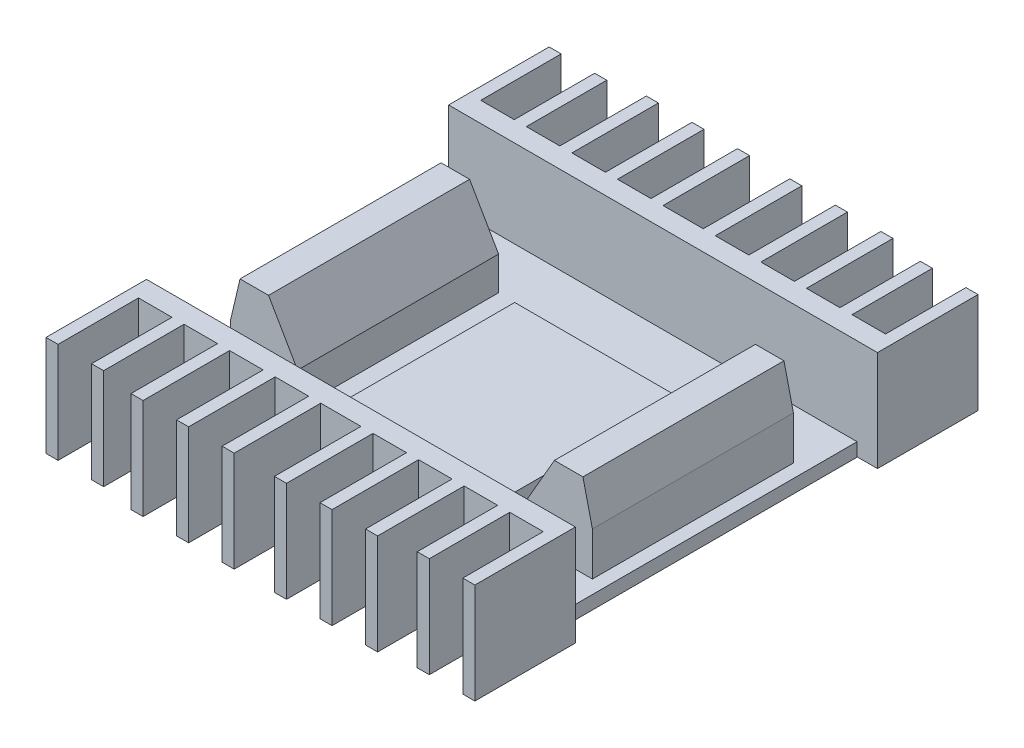
SolidWorks part; units mm, degrees
ref_plane "Front Plane" through (0, 0, 0) normal (0, 0, 1) x (1, 0, 0)
ref_plane "Top Plane" through (0, 0, 0) normal (0, 1, 0) x (1, 0, 0)
ref_plane "Right Plane" through (0, 0, 0) normal (1, 0, 0) x (0, 0, -1)
ref_plane "Plane1" through (0, 0, 0) normal (0, 0, 1) x (1, 0, 0)
ref_plane "Plane2" through (0, 0, 0) normal (0, 1, 0) x (1, 0, 0)
ref_plane "Plane3" through (0, 0, 0) normal (1, 0, 0) x (0, 0, -1)
sketch "Sketch2" plane through (0, 0, 0) normal (0, 1, 0) x (1, 0, 0)
  line L0 (-55, 0) -> (55, 0) construction
  line L2 (-57.5797, 0) -> (0.4203, 0)
  line L3 (-57.5797, 0) -> (-57.5797, -45)
  line L4 (-57.5797, -45) -> (0.4203, -45)
  line L5 (0.4203, 0) -> (0.4203, -45)
  dimension "D1" = 58
  dimension "D2" = 45
extrude "Boss-Extrude1" add sketch "Sketch2" along normal blind 2
sketch "Sketch3" plane through (0, 0, 0) normal (0, 1, 0) x (1, 0, 0)
  line L0 (3.4203, -45.0399) -> (-60.5797, -45.0399)
  line L1 (0.4203, -45) -> (0.4203, 0) construction
  line L2 (3.4203, -45.0399) -> (3.4203, -60.0399)
  line L3 (3.4203, -60.0399) -> (1.6203, -60.0399)
  line L4 (1.6203, -60.0399) -> (1.6203, -48.0399)
  line L5 (1.6203, -48.0399) -> (-3.3797, -48.0399)
  line L6 (-3.3797, -48.0399) -> (-3.3797, -60.0399)
  line L7 (-3.3797, -60.0399) -> (-5.1797, -60.0399)
  line L8 (-5.1797, -60.0399) -> (-5.1797, -48.0399)
  line L9 (-5.1797, -48.0399) -> (-10.1797, -48.0399)
  line L10 (-10.1797, -48.0399) -> (-10.1797, -60.9537)
  line L11 (-10.1797, -60.9537) -> (-11.9797, -60.9537)
  line L12 (-11.9797, -60.9537) -> (-11.9797, -48.0399)
  line L13 (-11.9797, -48.0399) -> (-16.9797, -48.0399)
  line L14 (-16.9797, -48.0399) -> (-16.9797, -60.9537)
  line L15 (-16.9797, -60.9537) -> (-18.7797, -60.9537)
  line L16 (-18.7797, -60.9537) -> (-18.7797, -48.0399)
  line L17 (-18.7797, -48.0399) -> (-23.7797, -48.0399)
  line L18 (-23.7797, -48.0399) -> (-23.7797, -60.9537)
  line L19 (-23.7797, -60.9537) -> (-25.5797, -60.9537)
  line L20 (-25.5797, -60.9537) -> (-25.5797, -48.0399)
  line L21 (-25.5797, -48.0399) -> (-31.5797, -48.0399)
  line L22 (-60.5797, -45.0399) -> (-60.5797, -60.0399)
  line L23 (-60.5797, 15.0399) -> (-58.7797, 15.0399)
  line L24 (0.4203, -22.5) -> (-68.2434, -22.5) construction
  line L25 (-28.5797, 19.0663) -> (-28.5797, -64.0663) construction
  line L26 (-58.7797, 15.0399) -> (-58.7797, 3.0399)
  line L27 (-57.5797, 0) -> (-57.5797, -45) construction
  line L28 (-31.5797, -60.9537) -> (-31.5797, -48.0399)
  line L29 (-33.3797, -60.9537) -> (-31.5797, -60.9537)
  line L30 (-33.3797, -48.0399) -> (-33.3797, -60.9537)
  line L31 (-38.3797, -48.0399) -> (-33.3797, -48.0399)
  line L32 (-38.3797, -60.9537) -> (-38.3797, -48.0399)
  line L33 (-40.1797, -60.9537) -> (-38.3797, -60.9537)
  line L34 (-40.1797, -48.0399) -> (-40.1797, -60.9537)
  line L35 (-45.1797, -48.0399) -> (-40.1797, -48.0399)
  line L36 (-45.1797, -60.9537) -> (-45.1797, -48.0399)
  line L37 (-46.9797, -60.9537) -> (-45.1797, -60.9537)
  line L38 (-46.9797, -48.0399) -> (-46.9797, -60.9537)
  line L39 (-51.9797, -48.0399) -> (-46.9797, -48.0399)
  line L40 (-51.9797, -60.0399) -> (-51.9797, -48.0399)
  line L41 (-53.7797, -60.0399) -> (-51.9797, -60.0399)
  line L42 (-53.7797, -48.0399) -> (-53.7797, -60.0399)
  line L43 (-58.7797, -48.0399) -> (-53.7797, -48.0399)
  line L44 (-58.7797, -60.0399) -> (-58.7797, -48.0399)
  line L45 (-60.5797, -60.0399) -> (-58.7797, -60.0399)
  line L46 (-58.7797, 3.0399) -> (-53.7797, 3.0399)
  line L47 (-53.7797, 3.0399) -> (-53.7797, 15.0399)
  line L48 (-53.7797, 15.0399) -> (-51.9797, 15.0399)
  line L49 (-51.9797, 15.0399) -> (-51.9797, 3.0399)
  line L50 (-51.9797, 3.0399) -> (-46.9797, 3.0399)
  line L51 (-46.9797, 3.0399) -> (-46.9797, 15.9537)
  line L52 (-46.9797, 15.9537) -> (-45.1797, 15.9537)
  line L53 (-45.1797, 15.9537) -> (-45.1797, 3.0399)
  line L54 (-45.1797, 3.0399) -> (-40.1797, 3.0399)
  line L55 (-40.1797, 3.0399) -> (-40.1797, 15.9537)
  line L56 (-40.1797, 15.9537) -> (-38.3797, 15.9537)
  line L57 (-38.3797, 15.9537) -> (-38.3797, 3.0399)
  line L58 (-38.3797, 3.0399) -> (-33.3797, 3.0399)
  line L59 (-33.3797, 3.0399) -> (-33.3797, 15.9537)
  line L60 (-33.3797, 15.9537) -> (-31.5797, 15.9537)
  line L61 (-31.5797, 15.9537) -> (-31.5797, 3.0399)
  line L62 (-60.5797, 0.0399) -> (-60.5797, 15.0399)
  line L63 (-25.5797, 3.0399) -> (-31.5797, 3.0399)
  line L64 (-25.5797, 15.9537) -> (-25.5797, 3.0399)
  line L65 (-23.7797, 15.9537) -> (-25.5797, 15.9537)
  line L66 (-23.7797, 3.0399) -> (-23.7797, 15.9537)
  line L67 (-18.7797, 3.0399) -> (-23.7797, 3.0399)
  line L68 (-18.7797, 15.9537) -> (-18.7797, 3.0399)
  line L69 (-16.9797, 15.9537) -> (-18.7797, 15.9537)
  line L70 (-16.9797, 3.0399) -> (-16.9797, 15.9537)
  line L71 (-11.9797, 3.0399) -> (-16.9797, 3.0399)
  line L72 (-11.9797, 15.9537) -> (-11.9797, 3.0399)
  line L73 (-10.1797, 15.9537) -> (-11.9797, 15.9537)
  line L74 (-10.1797, 3.0399) -> (-10.1797, 15.9537)
  line L75 (-5.1797, 3.0399) -> (-10.1797, 3.0399)
  line L76 (-5.1797, 15.0399) -> (-5.1797, 3.0399)
  line L77 (-3.3797, 15.0399) -> (-5.1797, 15.0399)
  line L78 (-3.3797, 3.0399) -> (-3.3797, 15.0399)
  line L79 (1.6203, 3.0399) -> (-3.3797, 3.0399)
  line L80 (1.6203, 15.0399) -> (1.6203, 3.0399)
  line L81 (3.4203, 15.0399) -> (1.6203, 15.0399)
  line L82 (3.4203, 0.0399) -> (3.4203, 15.0399)
  line L83 (3.4203, 0.0399) -> (-60.5797, 0.0399)
  point P32 (-28.5797, -22.5)
  dimension "D1" = 64
  dimension "D2" = 3
  dimension "D3" = 29
  dimension "D4" = 1.8
  dimension "D5" = 5
  dimension "D6" = 3
  dimension "D7" = 15
  dimension "D8" = 12
extrude "Boss-Extrude2" add sketch "Sketch3" along normal blind 15 separate body
ref_plane "Plane4" through (0, 0, 7.5) normal (0, 0, 1) x (1, 0, 0)
sketch "Sketch4" plane through (0, 0, 7.5) normal (0, 0, 1) x (1, 0, 0)
  line L0 (-1.5797, 2) -> (-11.5797, 2)
  line L1 (0.4203, 2) -> (-57.5797, 2) construction
  line L2 (-11.5797, 2) -> (-11.5797, 7)
  line L3 (-11.5797, 7) -> (-7.2495, 14.5)
  line L4 (-7.2495, 14.5) -> (-2.9964, 14.5)
  line L5 (-2.9964, 14.5) -> (-1.5797, 8.4763)
  line L6 (-1.5797, 8.4763) -> (-1.5797, 2)
  line L7 (0.4203, 2) -> (0.4203, 0) construction
  line L8 (-28.5797, 0) -> (-28.5797, 19.4162) construction
  line L9 (35.2, 0) -> (-35.2, 0) construction
  line L10 (-57.5797, 2) -> (-57.5797, 0) construction
  line L11 (-55.5797, 8.4763) -> (-55.5797, 2)
  line L12 (-54.163, 14.5) -> (-55.5797, 8.4763)
  line L13 (-49.9098, 14.5) -> (-54.163, 14.5)
  line L14 (-45.5797, 7) -> (-49.9098, 14.5)
  line L15 (-45.5797, 2) -> (-45.5797, 7)
  line L16 (-55.5797, 2) -> (-45.5797, 2)
  dimension "D1" = 5
  dimension "D2" = 4.2532
  dimension "D3" = 7.5
  dimension "D4" = 2
  dimension "D5" = 10
  dimension "D6" = 150
  dimension "D7" = 29
extrude "Boss-Extrude3" add sketch "Sketch4" along normal blind 30
sketch "Sketch5" plane through (0, 2, 0) normal (0, 1, 0) x (1, 0, 0)
  line L1 (-16.6057, -35.8994) -> (-41.1238, -35.8994)
  line L2 (-16.6057, -35.8994) -> (-16.6057, -9.5568)
  line L3 (-16.6057, -9.5568) -> (-41.1238, -9.5568)
  line L4 (-41.1238, -35.8994) -> (-41.1238, -9.5568)
extrude "Boss-Extrude4" add sketch "Sketch5" along normal blind 2
